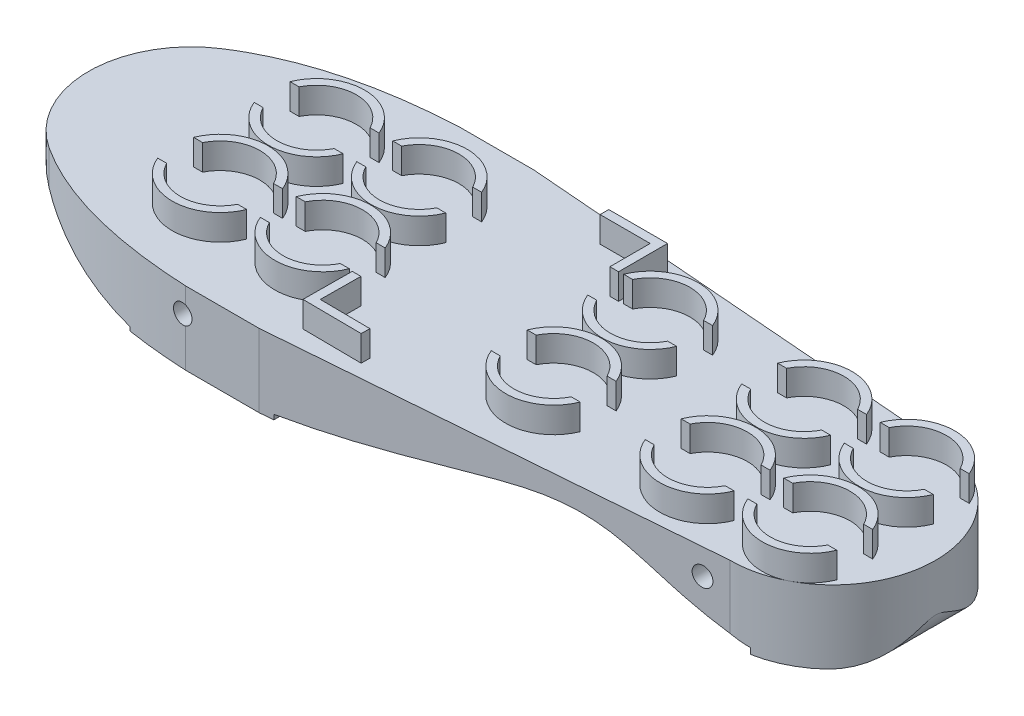
SolidWorks part; units mm, degrees
ref_plane "Front Plane" through (0, 0, 0) normal (0, 0, 1) x (1, 0, 0)
ref_plane "Top Plane" through (0, 0, 0) normal (0, 1, 0) x (1, 0, 0)
ref_plane "Right Plane" through (0, 0, 0) normal (1, 0, 0) x (0, 0, -1)
sketch "Sketch1" plane through (0, 0, 0) normal (0, 0, 1) x (1, 0, 0)
  line L0 (-126.8766, 0) -> (12.8234, 0) construction
  line L1 (-44.3266, 0) -> (-44.3266, 56.4646) construction
  line L2 (-126.8766, 0) -> (-126.8766, 88.0661) construction
  line L3 (-126.8766, 0) -> (-190.3766, 0) construction
  line L4 (-189.8988, 15.8678) -> (-188.6488, 18.079)
  line L5 (18.4538, 6.7485) -> (20.9624, 6.35)
  line L6 (-188.6488, 18.079) -> (20.9624, 18.079)
  line L7 (20.9624, 18.079) -> (20.9624, 6.35)
  line L8 (-109.0966, 1.2193) -> (-109.0966, 0)
  line L9 (-145.9266, 0.9315) -> (-145.9266, 0)
  line L10 (-145.9266, 0) -> (-109.0966, 0)
  line L11 (0.1234, 1.4718) -> (0.1234, 0)
  line L12 (0.1234, 0) -> (12.8234, 0)
  line L13 (0.1234, 0) -> (12.8234, 0)
  line L14 (12.8234, 0) -> (12.4342, 0.0891)
  spline S0 degree 3 poles (-126.8766, 0) (-92.1529, 0.983) (-25.5411, 24.1181) (-22.4447, 2.2803) (12.8234, 0) knots 0 0 0 0 0.394898 1 1 1 1
  spline S1 degree 3 poles (-126.8766, 0) (-149.6182, -0.6438) (-170.303, 4.7905) (-189.8988, 15.8678) knots 0 0 0 0 1 1 1 1
  spline S2 degree 2 poles (12.8234, 0) (19.9747, 0.1316) (20.9624, 6.35) knots 0 0 0 1 1 1
  spline S3 degree 1 poles (12.8781, 2.5418) (18.4538, 6.7485) knots 0 0 1 1 construction
  spline S4 degree 1 poles (-126.9485, 2.539) (12.8781, 2.5418) knots 0 0 1 1 construction
  spline S5 degree 1 poles (-126.9485, 2.539) (-188.6488, 18.079) knots 0 0 1 1 construction
  spline S6 degree 3 poles (18.4538, 6.7485) (18.4237, 6.5586) (18.3475, 6.1682) (18.162, 5.5017) (17.8662, 4.8046) (17.4352, 4.1669) (16.9153, 3.6581) (16.2528, 3.2313) (15.3876, 2.8808) (14.4609, 2.6735) (13.6037, 2.574) (13.1152, 2.5479) (12.8781, 2.5418) knots 0.00843 0.00843 0.00843 0.00843 0.070403 0.132376 0.256322 0.380269 0.504215 0.628161 0.752107 0.876054 0.938027 1 1 1 1
  spline S7 degree 3 poles (12.8781, 2.5418) (12.4374, 2.5706) (11.5486, 2.6331) (9.8346, 2.7704) (7.7657, 2.9672) (5.4088, 3.24) (2.4207, 3.6488) (-1.0377, 4.2374) (-4.7959, 5.0454) (-8.2129, 5.9337) (-12.3833, 7.1977) (-17.0046, 8.8785) (-22.0236, 10.9085) (-26.9256, 12.7903) (-32.0873, 14.3199) (-37.8306, 15.2554) (-44.4196, 15.3961) (-52.2167, 14.5337) (-61.3362, 12.7018) (-71.7854, 10.3287) (-83.5732, 7.7509) (-94.4945, 5.7296) (-103.8789, 4.3642) (-111.2352, 3.5102) (-117.6345, 2.9768) (-122.898, 2.6796) (-125.6041, 2.577) (-126.9485, 2.539) knots 0 0 0 0 0.007808 0.015615 0.03123 0.046845 0.06246 0.09369 0.12492 0.156151 0.187381 0.249841 0.312301 0.374761 0.437222 0.499682 0.562142 0.624602 0.687063 0.749523 0.811983 0.874443 0.905673 0.936904 0.968134 0.983749 0.999364 0.999364 0.999364 0.999364
  spline S8 degree 3 poles (-126.9485, 2.539) (-128.3332, 2.4998) (-131.1159, 2.4671) (-136.5855, 2.5879) (-143.317, 3.0839) (-151.2187, 4.2262) (-158.9647, 5.9104) (-166.5683, 8.1324) (-174.043, 10.8882) (-180.1793, 13.6288) (-185.0312, 16.082) (-187.4528, 17.4028) (-188.6488, 18.079) knots 0 0 0 0 0.0625 0.125 0.25 0.375 0.5 0.625 0.75 0.875 0.9375 1 1 1 1
  dimension "D8" = 2.54
  dimension "D1" = 139.7
  dimension "D2" = 82.55
  dimension "D3" = 57.15
  dimension "D4" = 12.7
  dimension "D5" = 63.5
  dimension "D6" = 15.875
  dimension "D7" = 6.35
  dimension "D9" = 19.05
  dimension "D10" = 17.78
  dimension "D11" = 12.7
extrude "Boss-Extrude1" add sketch "Sketch1" against normal blind 67.945 contours S8 S7 S6 L5 L7 L6 | S7 S8 L4 S1 S0 S2 L5 S6 | S0 L10 L8 | L10 S1 L9 | S0 L11 L12
sketch "Sketch2" plane through (0, 0, 0) normal (0, 1, 0) x (1, 0, 0)
  line L0 (-188.6488, 33.9725) -> (32.5563, 33.9725) construction
  line L2 (-4.4376, 59.3725) -> (-4.4376, 8.5725) construction
  line L4 (-112.4488, 33.9725) -> (-112.4488, 110.343) construction
  line L5 (-4.4376, 59.3725) -> (-112.4488, 67.945)
  line L7 (-4.4376, 8.5725) -> (-112.4488, 0)
  arc A0 (-4.4376, 59.3725) -> (-4.4376, 8.5725) centre (-4.4376, 33.9725) cw
  arc A1 (-177.1418, 12.7088) -> (-177.1418, 55.2362) centre (-163.2488, 33.9725) cw
  spline S0 degree 3 poles (-177.1418, 55.2362) (-158.5567, 67.379) (-133.3488, 68.7947) (-112.4488, 67.945) knots 0 0 0 0 1 1 1 1
  spline S1 degree 3 poles (-177.1418, 12.7088) (-158.5567, 0.566) (-133.3488, -0.8497) (-112.4488, 0) knots 0 0 0 0 1 1 1 1
  dimension "D1" = 25.4
  dimension "D3" = 25.4
extrude "Cut-Extrude4" cut sketch "Sketch2" along normal through all flip side to cut
sketch "Sketch4" plane through (0, 18.079, 0) normal (0, 1, 0) x (1, 0, 0)
  line L0 (-188.6488, 33.9725) -> (20.9624, 33.9725) construction
  line L1 (20.9624, 33.9725) -> (20.9624, 97.4678) construction
  line L2 (-10.7876, 33.9725) -> (-10.7876, 119.4054) construction
  line L3 (-61.5876, 33.9725) -> (-61.5876, 109.518) construction
  line L4 (-61.5876, 45.9105) -> (-23.4876, 45.9105) construction
  line L5 (-131.4376, 33.9725) -> (-131.4376, 103.6474) construction
  line L6 (-118.7376, 45.9105) -> (-61.5876, 45.9105) construction
  circle A2 centre (1.9124, 45.9105) radius 9.3345
  circle A3 centre (-23.4876, 45.9105) radius 9.3345
  circle A4 centre (-61.5876, 45.9105) radius 9.3345
  circle A5 centre (-118.7376, 45.9105) radius 9.3345
  circle A6 centre (-144.1376, 45.9105) radius 9.3345
  circle A7 centre (1.9124, 45.9105) radius 11.8745
  circle A8 centre (-23.4876, 45.9105) radius 11.8745
  circle A9 centre (-61.5876, 45.9105) radius 11.8745
  circle A10 centre (-118.7376, 45.9105) radius 11.8745
  circle A11 centre (-144.1376, 45.9105) radius 11.8745
  circle A12 centre (1.9124, 22.0345) radius 9.3345
  circle A13 centre (1.9124, 22.0345) radius 11.8745
  circle A14 centre (-23.4876, 22.0345) radius 9.3345
  circle A15 centre (-23.4876, 22.0345) radius 11.8745
  circle A16 centre (-61.5876, 22.0345) radius 9.3345
  circle A17 centre (-61.5876, 22.0345) radius 11.8745
  circle A18 centre (-118.7376, 22.0345) radius 9.3345
  circle A19 centre (-118.7376, 22.0345) radius 11.8745
  circle A20 centre (-144.1376, 22.0345) radius 9.3345
  circle A21 centre (-144.1376, 22.0345) radius 11.8745
  dimension "D1" = 18.669
  dimension "D5" = 18.669
  dimension "D8" = 18.669
  dimension "D2" = 31.75
  dimension "D3" = 11.938
  dimension "D4" = 12.7
  dimension "D6" = 82.55
  dimension "D7" = 152.4
  dimension "D9" = 12.7
  dimension "D10" = 2.54
  dimension "D11" = 2.54
  dimension "D12" = 2.54
  dimension "D13" = 2.54
  dimension "D14" = 2.54
extrude "Boss-Extrude4" add sketch "Sketch4" along normal blind 6.35
sketch "Sketch6" plane through (0, 18.079, 0) normal (0, 1, 0) x (1, 0, 0)
  line L0 (41.044, 50.3555) -> (-164.2193, 50.3555)
  line L1 (41.044, 50.3555) -> (41.044, 41.4655)
  line L2 (-164.2193, 50.3555) -> (-164.2193, 41.4655)
  line L3 (41.044, 41.4655) -> (-164.2193, 41.4655)
  line L4 (41.044, 50.3555) -> (-164.2193, 41.4655) construction
  line L5 (-164.2193, 50.3555) -> (41.044, 41.4655) construction
  line L6 (-163.2488, 33.9725) -> (29.2146, 33.9725) construction
  line L7 (41.044, 17.5895) -> (41.044, 26.4795)
  line L8 (41.044, 26.4795) -> (-164.2193, 26.4795)
  line L9 (-164.2193, 17.5895) -> (-164.2193, 26.4795)
  line L10 (41.044, 17.5895) -> (-164.2193, 17.5895)
  point P1 (-61.5876, 45.9105)
  dimension "D1" = 8.89
extrude "Cut-Extrude2" cut sketch "Sketch6" along normal through all
sketch "Sketch7" plane through (0, 0, 0) normal (1, 0, 0) x (0, 0, -1)
  line L0 (33.9725, 18.079) -> (33.9725, -8.8205) construction
  line L1 (59.3725, 18.079) -> (8.5725, 18.079) construction
  circle A0 centre (33.9725, 6.8622) radius 2.1803
extrude "Boss-Extrude5" add sketch "Sketch7" against normal blind 109.728
sketch "Sketch8" plane through (0, 0, 0) normal (0, 1, 0) x (1, 0, 0)
  line L0 (-217.8326, -9.4652) -> (46.654, -21.2065)
  line L1 (-217.8326, -9.4652) -> (-213.4136, 90.0784)
  line L2 (46.654, -21.2065) -> (51.073, 78.3372)
  line L3 (-213.4136, 90.0784) -> (51.073, 78.3372)
  line L4 (-217.8326, -9.4652) -> (51.073, 78.3372) construction
  line L5 (46.654, -21.2065) -> (-213.4136, 90.0784) construction
  point P1 (-83.3798, 34.436)
sketch "Sketch9" plane through (0, 18.079, 0) normal (0, 1, 0) x (1, 0, 0)
  line L0 (-188.6488, 33.9725) -> (-83.3798, 34.436) construction
  line L1 (-73.7602, 62.379) -> (-73.7602, 50.2608)
  line L2 (-88.3008, 62.379) -> (-73.7602, 62.379)
  line L3 (-73.7602, 50.2608) -> (-75.9059, 50.2608)
  line L4 (-75.9059, 50.2608) -> (-75.9059, 60.2333)
  line L5 (-75.9059, 60.2333) -> (-88.3008, 60.2333)
  line L6 (-105.3815, 62.379) -> (-76.3002, 6.4272) construction
  line L7 (-102.8415, 14.7476) -> (-73.7602, 62.379) construction
  line L8 (-88.3008, 60.2333) -> (-88.3008, 62.379)
  line L15 (-88.3008, 38.5633) -> (-88.3008, 50.2608) construction
  line L16 (-92.3383, 7.3039) -> (-92.3572, 5.1583)
  line L17 (-92.3572, 5.1583) -> (-106.8972, 5.2863)
  line L18 (-106.8972, 5.2863) -> (-106.7905, 17.4041)
  line L19 (-106.7905, 17.4041) -> (-104.6449, 17.3852)
  line L20 (-104.6449, 17.3852) -> (-104.7327, 7.4131)
  line L21 (-104.7327, 7.4131) -> (-92.3383, 7.3039)
  arc A1 (-177.1418, 55.2362) -> (-177.1418, 12.7088) centre (-163.2488, 33.9725) ccw construction
  point P2 (-90.8408, 34.4031)
extrude "Boss-Extrude7" add sketch "Sketch9" along normal blind 6.35 contours L2 L1 L3 L4 L5 L8 | L20 L21 L16 L17 L18 L19
sketch "Sketch10" plane through (0, 24.429, 0) normal (0, 1, 0) x (1, 0, 0)
  circle A0 centre (-144.1376, 45.9105) radius 9.8425
  arc A1 (-135.9294, 50.3555) -> (-152.3458, 50.3555) centre (-144.1376, 45.9105) ccw construction
  circle A2 centre (-118.7376, 45.9105) radius 9.8425
  circle A3 centre (-144.1376, 22.0345) radius 9.8425
  circle A4 centre (-118.7376, 22.0345) radius 9.8425
  circle A5 centre (-23.4876, 45.9105) radius 9.8425
  circle A6 centre (-23.4876, 22.0345) radius 9.8425
  circle A7 centre (1.9124, 45.9105) radius 9.8425
  circle A8 centre (1.9124, 22.0345) radius 9.8425
  circle A9 centre (-61.5876, 22.0345) radius 9.8425
  circle A10 centre (-61.5876, 45.9105) radius 9.8425
  dimension "D1" = 0.508
extrude "Cut-Extrude5" cut sketch "Sketch10" against normal up to surface (6.35 mm away) up to face at (-101.2935, 18.079, -9.9918)
sketch "Sketch11" plane through (0, 0, 0) normal (0, 0, 1) x (1, 0, 0)
  line L0 (-133.1265, 21.254) -> (-129.7488, 21.254) construction
  line L1 (-133.1265, 24.429) -> (-133.1265, 18.079) construction
  line L2 (-129.7488, 18.079) -> (-129.7488, 24.429) construction
  line L3 (-131.4376, 21.254) -> (-131.4376, -7.8806) construction
  line L4 (-107.7265, 18.079) -> (-129.7488, 18.079) construction
  line L5 (-12.4765, 21.254) -> (-9.0988, 21.254) construction
  line L6 (-12.4765, 24.429) -> (-12.4765, 18.079) construction
  line L7 (-9.0988, 18.079) -> (-9.0988, 24.429) construction
  line L8 (-10.7876, 21.254) -> (-10.9094, 22.0327) construction
  line L9 (-10.7876, 21.254) -> (-10.7876, 7.6375) construction
  line L10 (-112.4488, 18.079) -> (-4.4376, 18.079) construction
  circle A0 centre (-131.4376, 11.729) radius 2.3813
  circle A1 centre (-10.7876, 11.729) radius 2.3813
  dimension "D1" = 4.7625
  dimension "D4" = 4.7625
  dimension "D2" = 6.35
  dimension "D3" = 6.35
extrude "Cut-Extrude6" cut sketch "Sketch11" against normal through all
